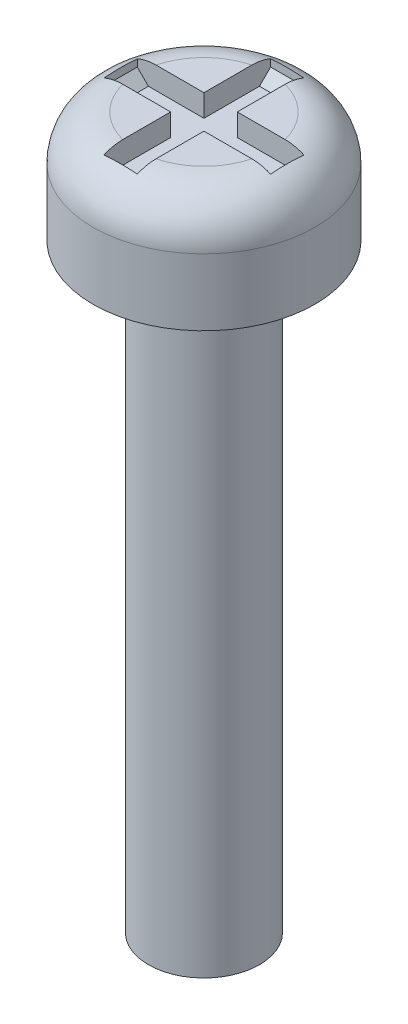
SolidWorks part; units mm, degrees
ref_plane "Front Plane" through (0, 0, 0) normal (0, 0, 1) x (1, 0, 0)
ref_plane "Top Plane" through (0, 0, 0) normal (0, 1, 0) x (1, 0, 0)
ref_plane "Right Plane" through (0, 0, 0) normal (1, 0, 0) x (0, 0, -1)
sketch "Sketch1" plane through (0, 0, 0) normal (0, 1, 0) x (1, 0, 0)
  circle A0 centre (0, 0) radius 2
  dimension "D1" = 4
extrude "Boss-Extrude1" add sketch "Sketch1" along normal blind 2
fillet "Fillet1" radius 0.8 1 edges at (0, 2, 2)
sketch "Sketch2" plane through (0, 2, 0) normal (0, 1, 0) x (1, 0, 0)
  line L1 (-1.5, 0.3) -> (1.5, 0.3)
  line L2 (-1.5, 0.3) -> (-1.5, -0.3)
  line L3 (-1.5, -0.3) -> (1.5, -0.3)
  line L4 (1.5, 0.3) -> (1.5, -0.3)
  line L5 (-1.5, 0.3) -> (1.5, -0.3) construction
  line L6 (-1.5, -0.3) -> (1.5, 0.3) construction
  line L7 (-0.3, -1.5) -> (0.3, -1.5)
  line L8 (-0.3, -1.5) -> (-0.3, 1.5)
  line L9 (-0.3, 1.5) -> (0.3, 1.5)
  line L10 (0.3, -1.5) -> (0.3, 1.5)
  line L11 (-0.3, -1.5) -> (0.3, 1.5) construction
  line L12 (-0.3, 1.5) -> (0.3, -1.5) construction
  point P0 (0, 0)
  point P6 (0, 0)
  circle M9 centre (0, 0) radius 1.2
  dimension "D1" = 1.5
  dimension "D2" = 0.6
extrude "Cut-Extrude1" cut sketch "Sketch2" against normal blind 0.4 contours L3 L8 L1 M9 | L1 L10 L8 M9 | L2 L3 L1 M9 | L10 L9 L8 M9 | L10 L3 L1 M9 | L4 L1 L3 M9 | L3 L10 L1 L8 | L10 L3 L8 M9 | L7 L10 L8 M9
chamfer "Chamfer1" distance 0.2 angle 45 4 edges at (0, 1.6, 1.5) (1.5, 1.6, 0) (-1.5, 1.6, 0) (0, 1.6, -1.5)
sketch "Sketch3" plane through (0, 0, 0) normal (0, -1, 0) x (1, 0, 0)
  circle A0 centre (0, 0) radius 1
  dimension "D1" = 2
extrude "Boss-Extrude2" add sketch "Sketch3" along normal blind 10.8
